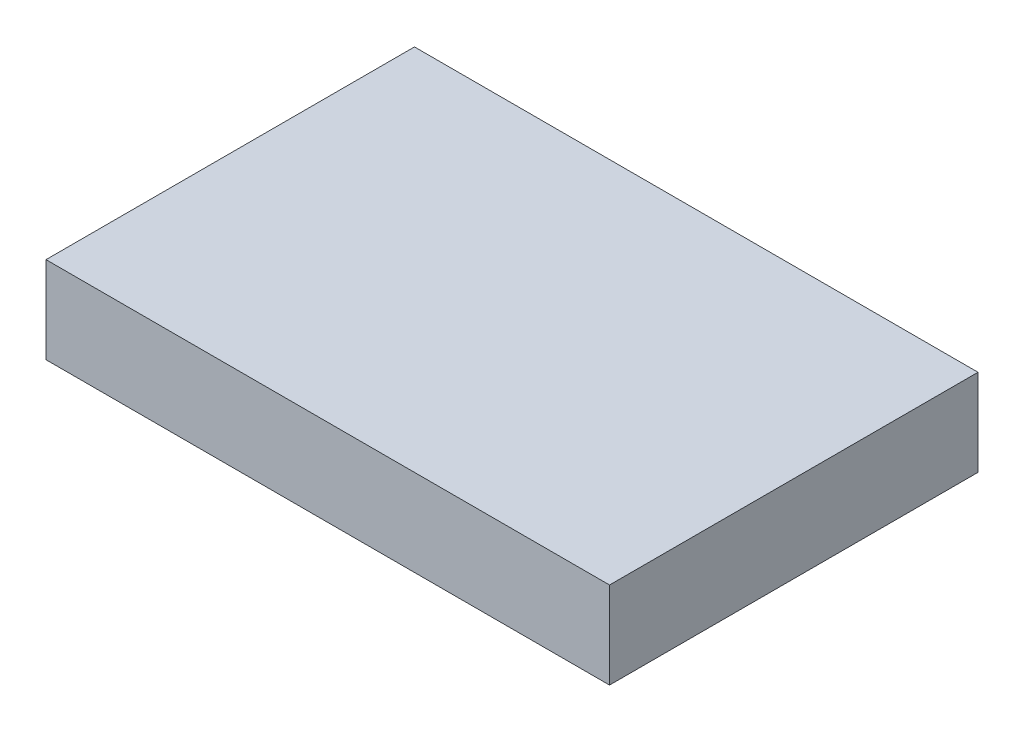
SolidWorks part; units mm, degrees
ref_plane "Front Plane" through (0, 0, 0) normal (0, 0, 1) x (1, 0, 0)
ref_plane "Top Plane" through (0, 0, 0) normal (0, 1, 0) x (1, 0, 0)
ref_plane "Right Plane" through (0, 0, 0) normal (1, 0, 0) x (0, 0, -1)
sketch "Sketch1" plane through (0, 0, 0) normal (0, 1, 0) x (1, 0, 0)
  line L1 (-13, 8.5) -> (13, 8.5)
  line L2 (-13, 8.5) -> (-13, -8.5)
  line L3 (-13, -8.5) -> (13, -8.5)
  line L4 (13, 8.5) -> (13, -8.5)
  line L5 (-13, 8.5) -> (13, -8.5) construction
  line L6 (-13, -8.5) -> (13, 8.5) construction
  point P0 (0, 0)
  dimension "D1" = 26
  dimension "D2" = 17
extrude "Boss-Extrude1" add sketch "Sketch1" along normal blind 4
